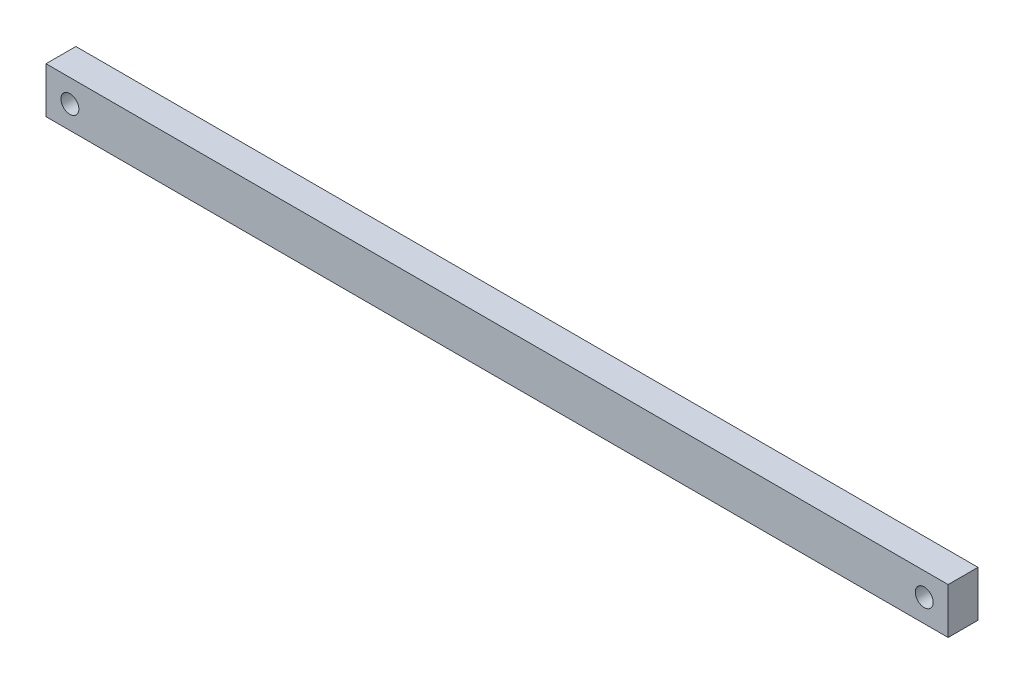
SolidWorks part; units mm, degrees
ref_plane "Front Plane" through (0, 0, 0) normal (0, 0, 1) x (1, 0, 0)
ref_plane "Top Plane" through (0, 0, 0) normal (0, 1, 0) x (1, 0, 0)
ref_plane "Right Plane" through (0, 0, 0) normal (1, 0, 0) x (0, 0, -1)
sketch "Sketch1" plane through (0, 0, 0) normal (0, 0, 1) x (1, 0, 0)
  line L0 (-539.0572, 0) -> (578.2468, 0) construction
  line L1 (0, 257.5318) -> (0, -317.5159) construction
  line L3 (-377.5, 19.1949) -> (377.5, 19.1949)
  line L4 (-377.5, 19.1949) -> (-377.5, -19.1949)
  line L5 (-377.5, -19.1949) -> (377.5, -19.1949)
  line L6 (377.5, 19.1949) -> (377.5, -19.1949)
  circle A0 centre (-357.5, 0) radius 7.5
  circle A1 centre (357.5, 0) radius 7.5
  point P5 (0, 0)
  dimension "D2" = 15
  dimension "D3" = 15
  dimension "D1" = 755
  dimension "D4" = 357.5
  dimension "D5" = 357.5
extrude "Boss-Extrude1" add sketch "Sketch1" along normal blind 25
